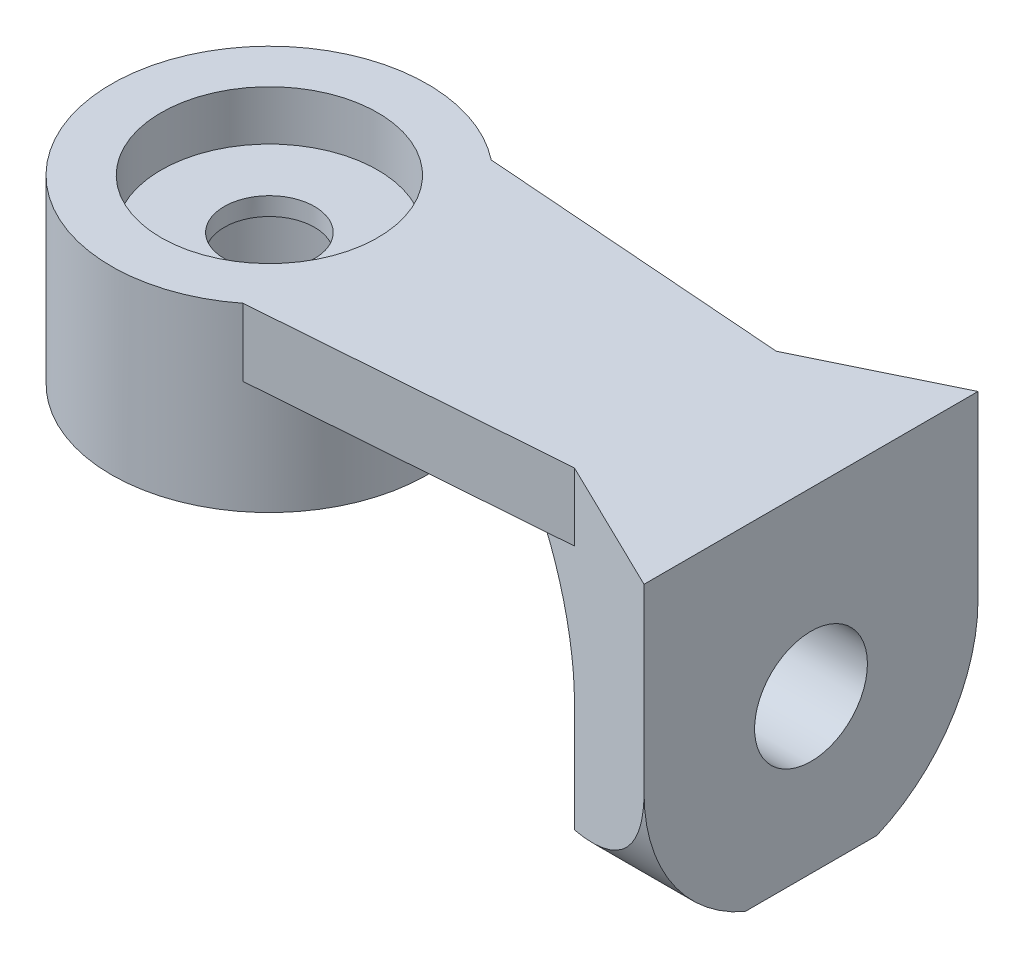
SolidWorks part; units mm, degrees
ref_plane "Спереди" through (0, 0, 0) normal (0, 0, 1) x (1, 0, 0)
ref_plane "Сверху" through (0, 0, 0) normal (0, 1, 0) x (1, 0, 0)
ref_plane "Справа" through (0, 0, 0) normal (1, 0, 0) x (0, 0, -1)
sketch "Эскиз1" plane through (0, 0, 0) normal (0, 1, 0) x (1, 0, 0)
  circle A0 centre (0, 0) radius 3.5
extrude "Бобышка-Вытянуть1" add sketch "Эскиз1" along normal blind 4
sketch "Эскиз2" plane through (0, 4, 0) normal (0, 1, 0) x (1, 0, 0)
  circle A0 centre (0, 0) radius 2.4
extrude "Вырез-Вытянуть1" cut sketch "Эскиз2" against normal blind 1.1
sketch "Эскиз3" plane through (0, 2.9, 0) normal (0, 1, 0) x (1, 0, 0)
  circle A0 centre (0, 0) radius 1
extrude "Вырез-Вытянуть2" cut sketch "Эскиз3" against normal through all
sketch "Эскиз4" plane through (0, 0, 0) normal (0, -1, 0) x (-1, 0, 0)
  circle A0 centre (0, 0) radius 2.3
extrude "Вырез-Вытянуть3" cut sketch "Эскиз4" against normal blind 2.5
sketch "Эскиз5" plane through (0, 4, 0) normal (0, 1, 0) x (1, 0, 0)
  line L0 (-3.5, 0) -> (16, 0) construction
  line L4 (14.15, 1.85) -> (2.1651, 2.75)
  line L5 (14.15, -1.85) -> (2.1651, -2.75)
  circle A0 centre (0, 0) radius 3.5 construction
  arc A1 (14.15, -1.85) -> (14.15, 1.85) centre (14.15, 0) ccw
  arc A2 (2.1651, -2.75) -> (2.1651, 2.75) centre (0, 0) ccw
  dimension "D1" = 19.5
extrude "Бобышка-Вытянуть2" add sketch "Эскиз5" against normal blind 1.5
sketch "Эскиз6" plane through (0, 4, 0) normal (0, 1, 0) x (1, 0, 0)
  line L0 (0, 0) -> (12, 0) construction
  line L1 (12, 0) -> (12, 3.7)
  line L2 (12, 0) -> (12, -3.7)
  line L3 (2.4, 0) -> (4.4, 0) construction
  line L4 (4.4, 0) -> (12, 3.7)
  line L6 (12, -3.7) -> (4.4, 0)
  circle A0 centre (0, 0) radius 2.4 construction
extrude "Бобышка-Вытянуть3" add sketch "Эскиз6" against normal blind 7.4
sketch "Эскиз9" plane through (0, 0, 0) normal (0, 0, 1) x (1, 0, 0)
  line L0 (0, 4) -> (3.5, 4)
  line L1 (2.4, 4) -> (-2.4, 4) construction
  line L4 (2.1651, 4) -> (8.9951, 4) construction
  line L6 (4.4, 2.5) -> (2.7249, -4.808)
  line L7 (12, -3.4) -> (9, -3.4)
  line L8 (4.4, -3.4) -> (12, -3.4) construction
  line L10 (9, -3.4) -> (8.9976, -0.4975)
  line L11 (5.9976, 2.5) -> (4.4, 2.5)
  line L12 (2.7249, -4.808) -> (9, -3.4)
  line L13 (9, -3.4) -> (9.0628, -3.3468)
  line L14 (12, 2.5) -> (12, 6.1144)
  line L15 (12, 6.1144) -> (17.6655, 6.1144)
  line L16 (17.6655, 6.1144) -> (17.6655, -1.4473)
  line L17 (17.6655, -1.4473) -> (12, 2.5)
  arc A0 (5.9976, 2.5) -> (8.9976, -0.4975) centre (5.9976, -0.5) cw
  point P17 (8.9951, 2.5)
  dimension "D1" = 3
extrude "Вырез-Вытянуть4" cut sketch "Эскиз9" against normal through all and the other way through all contours A0 L11 L6 L12 L10 | L17 L16 L15 L14
sketch "Эскиз10" plane through (12, 0, 0) normal (1, 0, 0) x (0, 0, -1)
  line L0 (0, 4) -> (0, 0)
  line L1 (-3.7, 4) -> (3.7, 4) construction
  line L2 (-3.7, 0) -> (-6.4273, -4.2909)
  line L3 (-6.4273, -4.2909) -> (7.2074, -4.8452)
  line L4 (7.2074, -4.8452) -> (3.7, 0)
  circle A0 centre (0, 0) radius 1.25
  arc A1 (-3.7, 0) -> (3.7, 0) centre (0, 0) ccw
extrude "Вырез-Вытянуть5" cut sketch "Эскиз10" against normal blind 7.4
